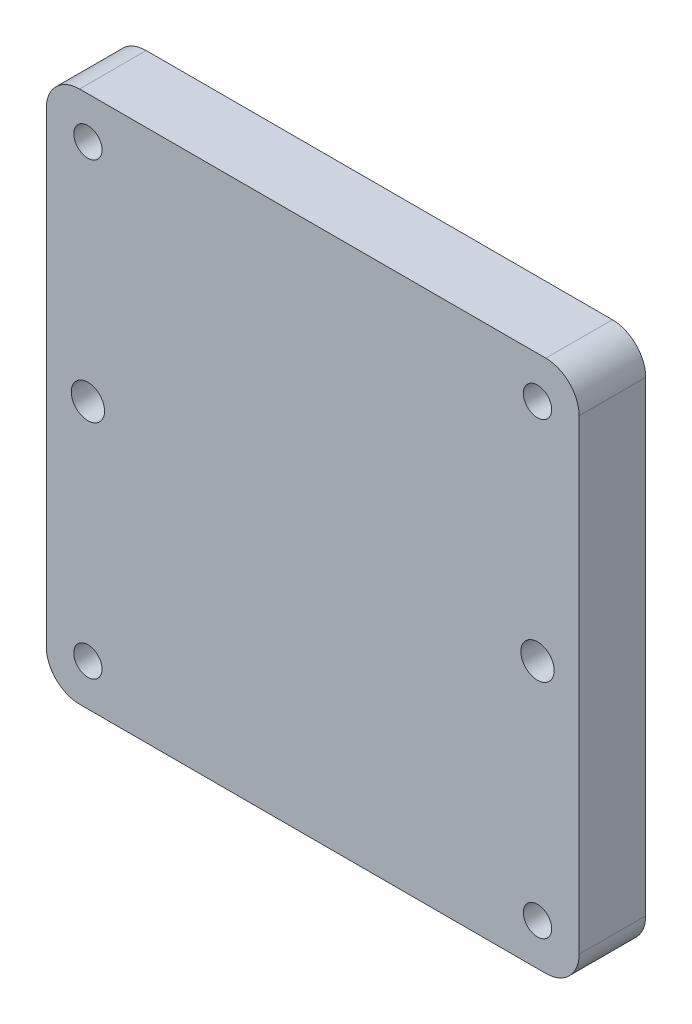
SolidWorks part; units mm, degrees
ref_plane "Front Plane" through (0, 0, 0) normal (0, 0, 1) x (1, 0, 0)
ref_plane "Top Plane" through (0, 0, 0) normal (0, 1, 0) x (1, 0, 0)
ref_plane "Right Plane" through (0, 0, 0) normal (1, 0, 0) x (0, 0, -1)
sketch "Top Plate Sketch Profile" plane through (0, 0, 114.3) normal (0, 0, 1) x (1, 0, 0)
  line L0 (50.8, 44.45) -> (50.8, -44.45) construction
  line L1 (44.45, -50.8) -> (-44.45, -50.8) construction
  line L2 (-50.8, -44.45) -> (-50.8, 44.45) construction
  line L3 (-44.45, 50.8) -> (44.45, 50.8) construction
  line L4 (50.8, 44.45) -> (50.8, -44.45)
  line L5 (44.45, -50.8) -> (-44.45, -50.8)
  line L6 (-50.8, -44.45) -> (-50.8, 44.45)
  line L7 (-44.45, 50.8) -> (44.45, 50.8)
  arc A0 (50.8, 44.45) -> (44.45, 50.8) centre (44.45, 44.45) ccw construction
  arc A1 (44.45, -50.8) -> (50.8, -44.45) centre (44.45, -44.45) ccw construction
  arc A2 (-50.8, -44.45) -> (-44.45, -50.8) centre (-44.45, -44.45) ccw construction
  arc A3 (-44.45, 50.8) -> (-50.8, 44.45) centre (-44.45, 44.45) ccw construction
  arc A4 (50.8, 44.45) -> (44.45, 50.8) centre (44.45, 44.45) ccw
  arc A5 (44.45, -50.8) -> (50.8, -44.45) centre (44.45, -44.45) ccw
  arc A6 (-50.8, -44.45) -> (-44.45, -50.8) centre (-44.45, -44.45) ccw
  arc A7 (-44.45, 50.8) -> (-50.8, 44.45) centre (-44.45, 44.45) ccw
  circle A8 centre (42.8625, 0) radius 3.175 construction
  circle A9 centre (42.8625, 0) radius 3.175
  circle A10 centre (-42.8625, 0) radius 3.175 construction
  circle A11 centre (-42.8625, 0) radius 3.175
  circle A12 centre (-42.8625, 42.8625) radius 2.6987
  circle A13 centre (42.8625, 42.8625) radius 2.6987
  circle A14 centre (42.8625, -42.8625) radius 2.6987
  circle A15 centre (-42.8625, -42.8625) radius 2.6987
  dimension "D1" = 5.3975
extrude "Top Plate Extrude" add sketch "Top Plate Sketch Profile" against normal blind 12.7
